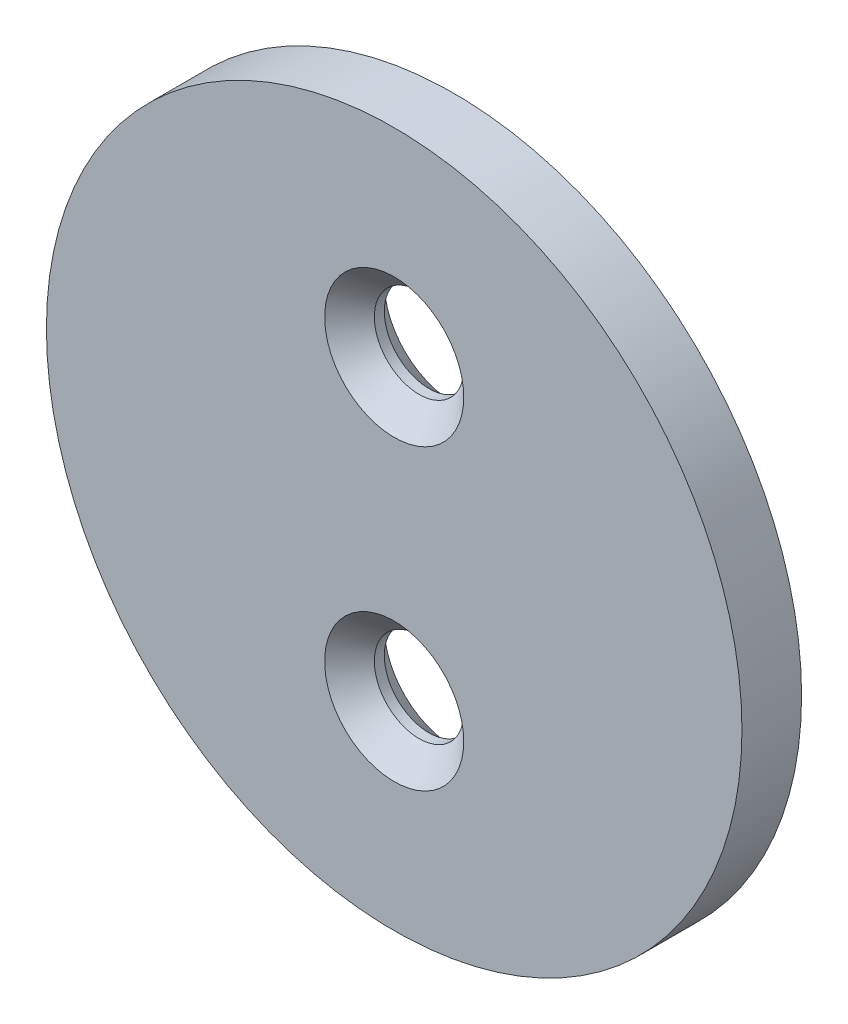
SolidWorks part; units mm, degrees
ref_plane "前视基准面" through (0, 0, 0) normal (0, 0, 1) x (1, 0, 0)
ref_plane "上视基准面" through (0, 0, 0) normal (0, 1, 0) x (1, 0, 0)
ref_plane "右视基准面" through (0, 0, 0) normal (1, 0, 0) x (0, 0, -1)
sketch "草图1" plane through (0, 0, 0) normal (0, 0, 1) x (1, 0, 0)
  circle A0 centre (0, 0) radius 7
extrude "凸台-拉伸1" add sketch "草图1" along normal blind 1.2
sketch "草图2" plane through (0, 0, 1.2) normal (0, 0, 1) x (1, 0, 0)
  line L0 (0, 0) -> (15.5284, 0) construction
  line L1 (0, 0) -> (0, 9.4324) construction
  circle A0 centre (0, 3) radius 0.9
  circle A1 centre (0, -3) radius 0.9
  dimension "D1" = 1.8
  dimension "D2" = 3
extrude "切除-拉伸1" cut sketch "草图2" against normal through all
fillet "圆角1" radius 0.5 4 edges at (0.9, 3, 0) (-0.9, -3, 0) (-0.9, -3, 1.2) (0.9, 3, 1.2) profile chamfer
